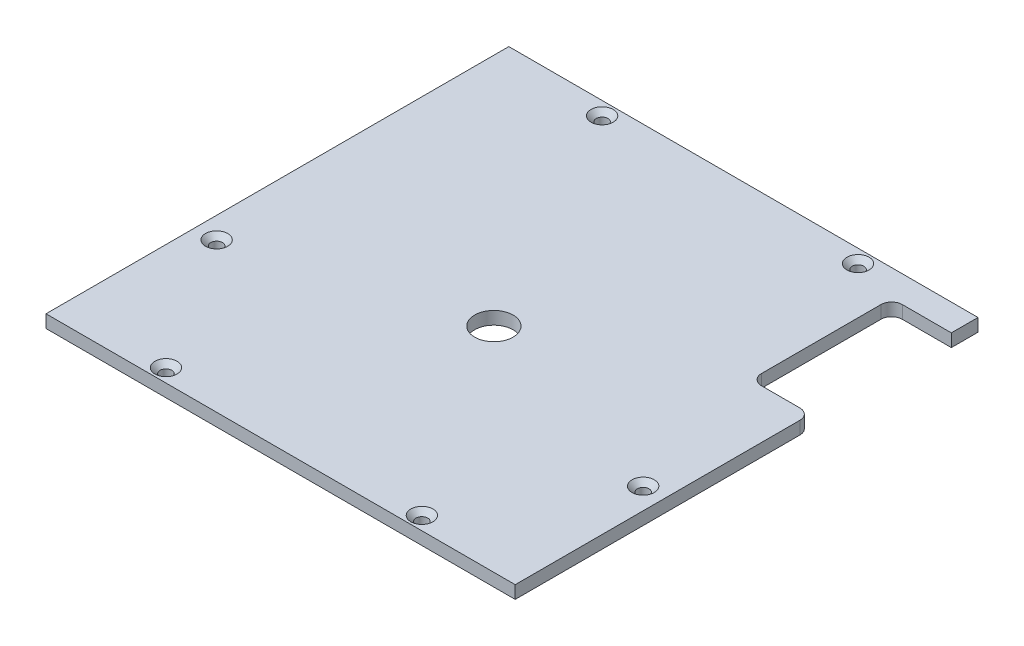
SolidWorks part; units mm, degrees
material "Acrylic (Medium-high impact)"
ref_plane "Front Plane" through (0, 0, 0) normal (0, 0, 1) x (1, 0, 0)
ref_plane "Top Plane" through (0, 0, 0) normal (0, 1, 0) x (1, 0, 0)
ref_plane "Right Plane" through (0, 0, 0) normal (1, 0, 0) x (0, 0, -1)
sketch "Sketch1" plane through (0, 0, 0) normal (0, 1, 0) x (1, 0, 0)
  line L1 (-110, -108.5) -> (110, -108.5)
  line L2 (-110, -108.5) -> (-110, 108.5)
  line L3 (-110, 108.5) -> (110, 108.5)
  line L4 (110, -108.5) -> (110, 108.5)
  line L5 (-110, -108.5) -> (110, 108.5) construction
  line L6 (-110, 108.5) -> (110, -108.5) construction
  point P0 (0, 0)
  dimension "D1" = 220
  dimension "D2" = 217
extrude "Bloco" add sketch "Sketch1" along normal blind 6
sketch "Sketch2" plane through (0, 6, 0) normal (0, 1, 0) x (1, 0, 0)
  line L1 (82, 96) -> (110, 96)
  line L2 (82, 96) -> (82, 30)
  line L3 (82, 30) -> (110, 30)
  line L4 (110, 96) -> (110, 30)
  line L6 (0, -108.5) -> (0, 0) construction
  line L8 (-110, -108.5) -> (110, -108.5) construction
  line L9 (110, 108.5) -> (-110, 108.5) construction
  line L10 (110, -108.5) -> (110, 108.5) construction
  circle A1 centre (0, -8.5) radius 9
  dimension "D4" = 100
  dimension "D5" = 18
  dimension "D1" = 12.5
  dimension "D2" = 66
  dimension "D3" = 28
extrude "Corte Motor" cut sketch "Sketch2" against normal through all
fillet "Raios 5mm" radius 5 3 edges at (110, 3, -30) (82, 3, -30) (82, 3, -96)
sketch "Posição dos Furos" plane through (0, 6, 0) normal (0, 1, 0) x (1, 0, 0)
  line L0 (0, -8.5) -> (0, 108.5) construction
  line L1 (110, 108.5) -> (-110, 108.5) construction
  line L2 (-110, 0) -> (110, 0) construction
  line L3 (-110, 108.5) -> (-110, -108.5) construction
  line L4 (110, -108.5) -> (110, 25) construction
  line L5 (-60, 102.25) -> (60, 102.25) construction
  line L6 (-110, -8.5) -> (110, -8.5) construction
  line L7 (-60, -102.25) -> (60, -102.25) construction
  circle A0 centre (-60, 102.25) radius 2.75
  circle A1 centre (60, 102.25) radius 2.75
  circle A2 centre (-100, -38.5) radius 2.75
  circle A3 centre (60, -102.25) radius 2.75
  circle A4 centre (-60, -102.25) radius 2.75
  circle A5 centre (100, -38.5) radius 2.75
  point P18 (0, -8.5)
  dimension "D1" = 60
  dimension "D2" = 60
  dimension "D3" = 5.5
  dimension "D4" = 6.25
  dimension "D5" = 30
  dimension "D6" = 10
hole_wizard "Furos Escareados - M5 Passante" positions "Sketch4" profile "Sketch5" countersink size "M5" standard "ANSI Metric" end condition through all
sketch "Sketch4" plane through (0, 6, 0) normal (0, 1, 0) x (1, 0, 0)
  point P0 (-100, -38.5)
  point P3 (-60, -102.25)
  point P6 (60, -102.25)
  point P9 (100, -38.5)
  point P12 (-60, 102.25)
  point P15 (60, 102.25)
sketch "Sketch5" plane through (-100, 6, 38.5) normal (1, 0, 0) x (0, 0, 1)
  line L0 (0, 0) -> (0, 6)
  line L1 (0, 6) -> (2.75, 6)
  line L2 (2.75, 6) -> (2.75, 2.45)
  line L3 (2.75, 2.45) -> (5.2, 0)
  line L5 (5.2, 0) -> (0, 0)
  line L6 (-2.75, 2.45) -> (-5.2, 0) construction
  line L11 (0, -6.35) -> (0, 107.95) construction
  dimension "Thru Hole Dia." = 5.5
  dimension "Thru Hole Depth" = 6
  dimension "Near C'Sink Dia." = 10.4
  dimension "Near C'Sink Angle" = 90
